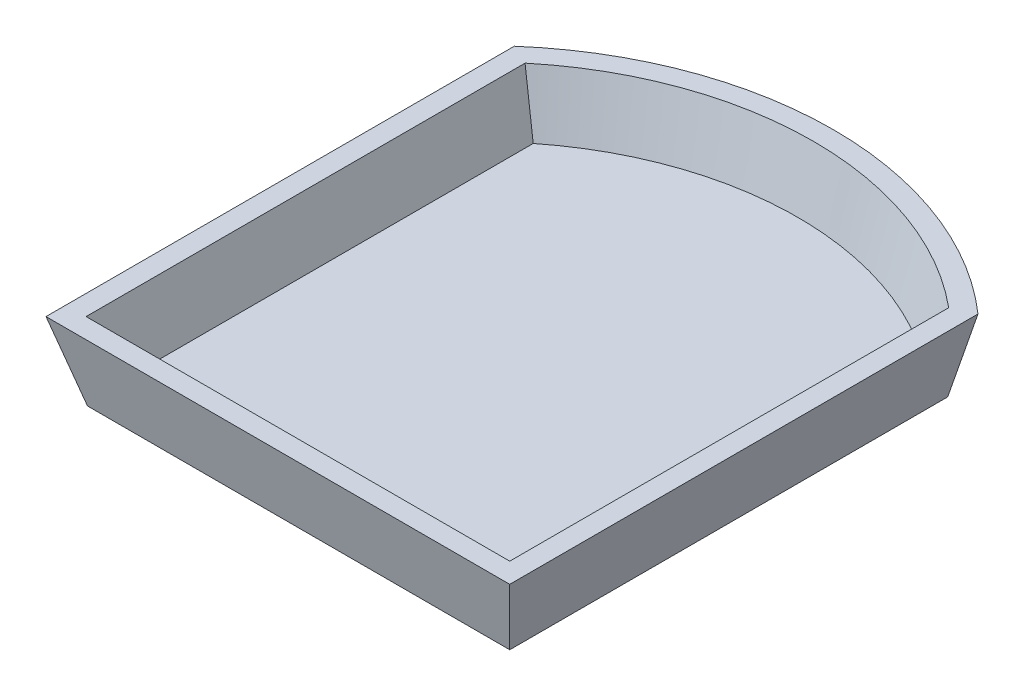
SolidWorks part; units mm, degrees
material "AISI 1020"
ref_plane "Front Plane" through (0, 0, 0) normal (0, 0, 1) x (1, 0, 0)
ref_plane "Top Plane" through (0, 0, 0) normal (0, 1, 0) x (1, 0, 0)
ref_plane "Right Plane" through (0, 0, 0) normal (1, 0, 0) x (0, 0, -1)
sketch "Sketch1" plane through (0, 0, 0) normal (0, 1, 0) x (1, 0, 0)
  line L1 (-109.0299, -113.0819) -> (109.0299, -113.0819)
  line L2 (-109.0299, -113.0819) -> (-109.0299, 113.0819)
  line L3 (-109.0299, 113.0819) -> (109.0299, 113.0819) construction
  line L4 (109.0299, -113.0819) -> (109.0299, 113.0819)
  line L5 (-109.0299, -113.0819) -> (109.0299, 113.0819) construction
  line L6 (-109.0299, 113.0819) -> (109.0299, -113.0819) construction
  arc A0 (-109.0299, 113.0819) -> (109.0299, 113.0819) centre (0, -18.4239) cw
  point P0 (0, 0)
extrude "Boss-Extrude1" add sketch "Sketch1" along normal blind 40 draft 15 draft outward yes
shell "Shell1" thickness 10
ref_plane "Plane1" through (0, 35, 0) normal (0, 1, 0) x (1, 0, 0)
